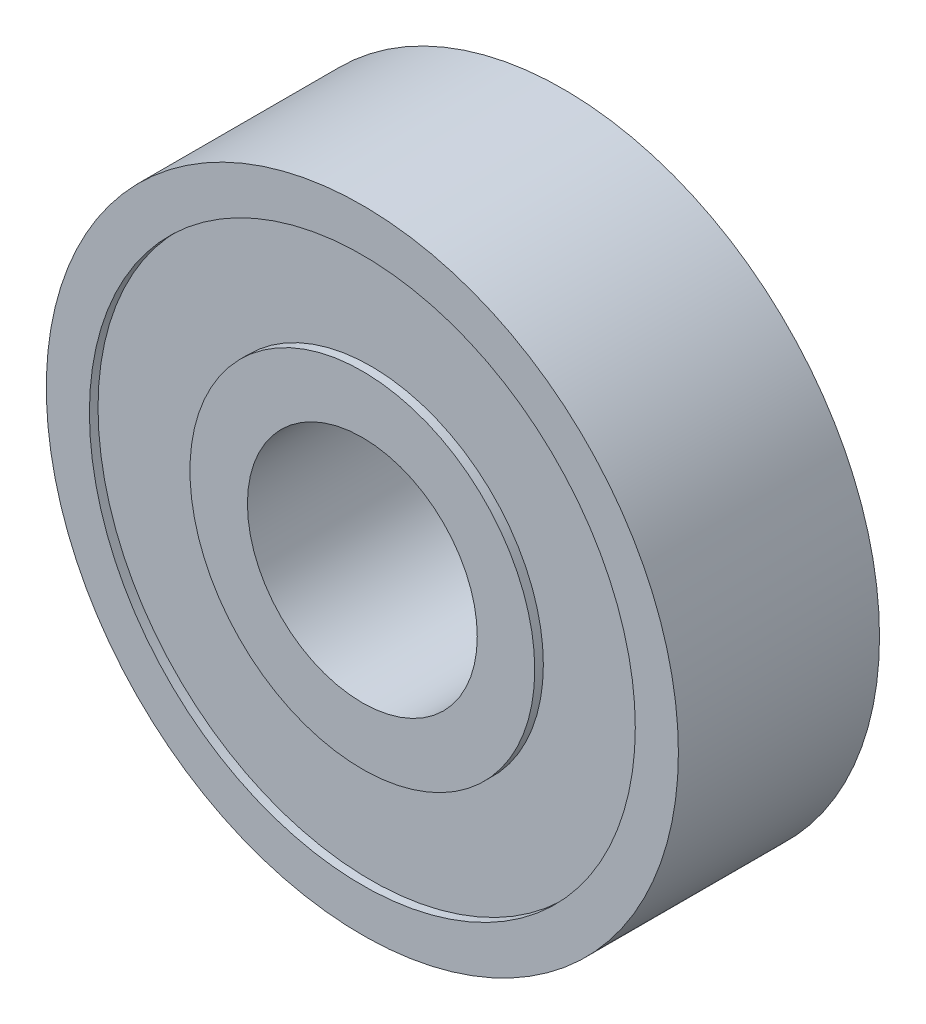
SolidWorks part; units mm, degrees
ref_plane "Front Plane" through (0, 0, 0) normal (0, 0, 1) x (1, 0, 0)
ref_plane "Top Plane" through (0, 0, 0) normal (0, 1, 0) x (1, 0, 0)
ref_plane "Right Plane" through (0, 0, 0) normal (1, 0, 0) x (0, 0, -1)
sketch "Sketch1" plane through (0, 0, 0) normal (0, 0, 1) x (1, 0, 0)
  circle A0 centre (0, 0) radius 11
  circle A1 centre (0, 0) radius 9.5
extrude "Outer_ring" add sketch "Sketch1" along normal blind 7
sketch "Sketch2" plane through (0, 0, 0) normal (0, 0, 1) x (1, 0, 0)
  circle A0 centre (0, 0) radius 6
  circle A1 centre (0, 0) radius 4
extrude "Inner_ring" add sketch "Sketch2" along normal blind 7
ref_plane "Plane_z0_3" through (0, 0, 0.3) normal (0, 0, 1) x (1, 0, 0)
sketch "Sketch3" plane through (0, 0, 0.3) normal (0, 0, 1) x (1, 0, 0)
  circle A0 centre (0, 0) radius 9.5
  circle A1 centre (0, 0) radius 6
extrude "Shields" add sketch "Sketch3" along normal blind 6.4
